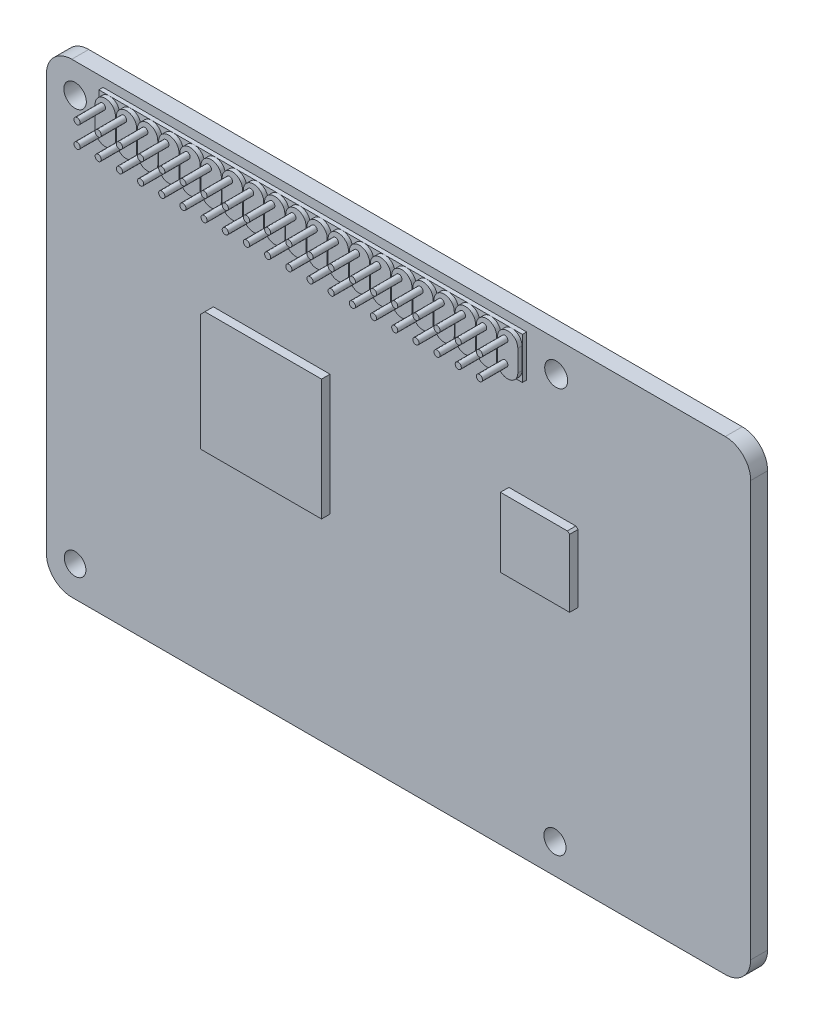
SolidWorks part; units mm, degrees
ref_plane "Plan de face" through (0, 0, 0) normal (0, 0, 1) x (1, 0, 0)
ref_plane "Plan de dessus" through (0, 0, 0) normal (0, 1, 0) x (1, 0, 0)
ref_plane "Plan de droite" through (0, 0, 0) normal (1, 0, 0) x (0, 0, -1)
sketch "Esquisse13" plane through (0, 0, 0) normal (0, 0, 1) x (1, 0, 0)
  line L1 (32.3051, 231.7529) -> (109.4451, 231.7529)
  line L2 (29.3051, 228.7529) -> (29.3051, 179.7529)
  line L3 (32.3051, 176.7529) -> (109.4451, 176.7529)
  line L4 (112.4451, 228.7529) -> (112.4451, 179.7529)
  arc A0 (112.4451, 228.7529) -> (109.4451, 231.7529) centre (109.4451, 228.7529) ccw
  arc A1 (112.4451, 179.7529) -> (109.4451, 176.7529) centre (109.4451, 179.7529) cw
  arc A2 (32.3051, 176.7529) -> (29.3051, 179.7529) centre (32.3051, 179.7529) cw
  arc A3 (32.3051, 231.7529) -> (29.3051, 228.7529) centre (32.3051, 228.7529) ccw
  dimension "D1" = 3
  dimension "D2" = 55
  dimension "D3" = 83.14
extrude "Boss.-Extru.6" add sketch "Esquisse13" along normal blind 2 separate body
sketch "Esquisse18" plane through (0, 0, 2) normal (0, 0, 1) x (1, 0, 0)
  line L0 (37.2566, 229.5258) -> (37.2566, 226.9968) construction
  line L1 (38.4539, 229.5258) -> (38.4539, 226.9968)
  line L2 (36.0594, 229.5258) -> (36.0594, 226.9968)
  line L3 (39.7566, 229.5258) -> (39.7566, 226.9968) construction
  line L4 (40.9539, 229.5258) -> (40.9539, 226.9968)
  line L5 (38.5594, 229.5258) -> (38.5594, 226.9968)
  line L6 (42.2566, 229.5258) -> (42.2566, 226.9968) construction
  line L7 (43.4539, 229.5258) -> (43.4539, 226.9968)
  line L8 (41.0594, 229.5258) -> (41.0594, 226.9968)
  line L9 (44.7566, 229.5258) -> (44.7566, 226.9968) construction
  line L10 (45.9539, 229.5258) -> (45.9539, 226.9968)
  line L11 (43.5594, 229.5258) -> (43.5594, 226.9968)
  line L12 (47.2566, 229.5258) -> (47.2566, 226.9968) construction
  line L13 (48.4539, 229.5258) -> (48.4539, 226.9968)
  line L14 (46.0594, 229.5258) -> (46.0594, 226.9968)
  line L15 (49.7566, 229.5258) -> (49.7566, 226.9968) construction
  line L16 (50.9539, 229.5258) -> (50.9539, 226.9968)
  line L17 (48.5594, 229.5258) -> (48.5594, 226.9968)
  line L18 (52.2566, 229.5258) -> (52.2566, 226.9968) construction
  line L19 (53.4539, 229.5258) -> (53.4539, 226.9968)
  line L20 (51.0594, 229.5258) -> (51.0594, 226.9968)
  line L21 (54.7566, 229.5258) -> (54.7566, 226.9968) construction
  line L22 (55.9539, 229.5258) -> (55.9539, 226.9968)
  line L23 (53.5594, 229.5258) -> (53.5594, 226.9968)
  line L24 (57.2566, 229.5258) -> (57.2566, 226.9968) construction
  line L25 (58.4539, 229.5258) -> (58.4539, 226.9968)
  line L26 (56.0594, 229.5258) -> (56.0594, 226.9968)
  line L27 (59.7566, 229.5258) -> (59.7566, 226.9968) construction
  line L28 (60.9539, 229.5258) -> (60.9539, 226.9968)
  line L29 (58.5594, 229.5258) -> (58.5594, 226.9968)
  line L30 (62.2566, 229.5258) -> (62.2566, 226.9968) construction
  line L31 (63.4539, 229.5258) -> (63.4539, 226.9968)
  line L32 (61.0594, 229.5258) -> (61.0594, 226.9968)
  line L33 (64.7566, 229.5258) -> (64.7566, 226.9968) construction
  line L34 (65.9539, 229.5258) -> (65.9539, 226.9968)
  line L35 (63.5594, 229.5258) -> (63.5594, 226.9968)
  line L36 (67.2566, 229.5258) -> (67.2566, 226.9968) construction
  line L37 (68.4539, 229.5258) -> (68.4539, 226.9968)
  line L38 (66.0594, 229.5258) -> (66.0594, 226.9968)
  line L39 (69.7566, 229.5258) -> (69.7566, 226.9968) construction
  line L40 (70.9539, 229.5258) -> (70.9539, 226.9968)
  line L41 (68.5594, 229.5258) -> (68.5594, 226.9968)
  line L42 (72.2566, 229.5258) -> (72.2566, 226.9968) construction
  line L43 (73.4539, 229.5258) -> (73.4539, 226.9968)
  line L44 (71.0594, 229.5258) -> (71.0594, 226.9968)
  line L45 (74.7566, 229.5258) -> (74.7566, 226.9968) construction
  line L46 (75.9539, 229.5258) -> (75.9539, 226.9968)
  line L47 (73.5594, 229.5258) -> (73.5594, 226.9968)
  line L48 (77.2566, 229.5258) -> (77.2566, 226.9968) construction
  line L49 (78.4539, 229.5258) -> (78.4539, 226.9968)
  line L50 (76.0594, 229.5258) -> (76.0594, 226.9968)
  line L51 (79.7566, 229.5258) -> (79.7566, 226.9968) construction
  line L52 (80.9539, 229.5258) -> (80.9539, 226.9968)
  line L53 (78.5594, 229.5258) -> (78.5594, 226.9968)
  line L54 (82.2566, 229.5258) -> (82.2566, 226.9968) construction
  line L55 (83.4539, 229.5258) -> (83.4539, 226.9968)
  line L56 (81.0594, 229.5258) -> (81.0594, 226.9968)
  line L57 (84.7566, 229.5258) -> (84.7566, 226.9968) construction
  line L58 (85.9539, 229.5258) -> (85.9539, 226.9968)
  line L59 (83.5594, 229.5258) -> (83.5594, 226.9968)
  arc A0 (38.4539, 229.5258) -> (36.0594, 229.5258) centre (37.2566, 229.5258) ccw
  arc A1 (36.0594, 226.9968) -> (38.4539, 226.9968) centre (37.2566, 226.9968) ccw
  arc A2 (40.9539, 229.5258) -> (38.5594, 229.5258) centre (39.7566, 229.5258) ccw
  arc A3 (38.5594, 226.9968) -> (40.9539, 226.9968) centre (39.7566, 226.9968) ccw
  arc A4 (43.4539, 229.5258) -> (41.0594, 229.5258) centre (42.2566, 229.5258) ccw
  arc A5 (41.0594, 226.9968) -> (43.4539, 226.9968) centre (42.2566, 226.9968) ccw
  arc A6 (45.9539, 229.5258) -> (43.5594, 229.5258) centre (44.7566, 229.5258) ccw
  arc A7 (43.5594, 226.9968) -> (45.9539, 226.9968) centre (44.7566, 226.9968) ccw
  arc A8 (48.4539, 229.5258) -> (46.0594, 229.5258) centre (47.2566, 229.5258) ccw
  arc A9 (46.0594, 226.9968) -> (48.4539, 226.9968) centre (47.2566, 226.9968) ccw
  arc A10 (50.9539, 229.5258) -> (48.5594, 229.5258) centre (49.7566, 229.5258) ccw
  arc A11 (48.5594, 226.9968) -> (50.9539, 226.9968) centre (49.7566, 226.9968) ccw
  arc A12 (53.4539, 229.5258) -> (51.0594, 229.5258) centre (52.2566, 229.5258) ccw
  arc A13 (51.0594, 226.9968) -> (53.4539, 226.9968) centre (52.2566, 226.9968) ccw
  arc A14 (55.9539, 229.5258) -> (53.5594, 229.5258) centre (54.7566, 229.5258) ccw
  arc A15 (53.5594, 226.9968) -> (55.9539, 226.9968) centre (54.7566, 226.9968) ccw
  arc A16 (58.4539, 229.5258) -> (56.0594, 229.5258) centre (57.2566, 229.5258) ccw
  arc A17 (56.0594, 226.9968) -> (58.4539, 226.9968) centre (57.2566, 226.9968) ccw
  arc A18 (60.9539, 229.5258) -> (58.5594, 229.5258) centre (59.7566, 229.5258) ccw
  arc A19 (58.5594, 226.9968) -> (60.9539, 226.9968) centre (59.7566, 226.9968) ccw
  arc A20 (63.4539, 229.5258) -> (61.0594, 229.5258) centre (62.2566, 229.5258) ccw
  arc A21 (61.0594, 226.9968) -> (63.4539, 226.9968) centre (62.2566, 226.9968) ccw
  arc A22 (65.9539, 229.5258) -> (63.5594, 229.5258) centre (64.7566, 229.5258) ccw
  arc A23 (63.5594, 226.9968) -> (65.9539, 226.9968) centre (64.7566, 226.9968) ccw
  arc A24 (68.4539, 229.5258) -> (66.0594, 229.5258) centre (67.2566, 229.5258) ccw
  arc A25 (66.0594, 226.9968) -> (68.4539, 226.9968) centre (67.2566, 226.9968) ccw
  arc A26 (70.9539, 229.5258) -> (68.5594, 229.5258) centre (69.7566, 229.5258) ccw
  arc A27 (68.5594, 226.9968) -> (70.9539, 226.9968) centre (69.7566, 226.9968) ccw
  arc A28 (73.4539, 229.5258) -> (71.0594, 229.5258) centre (72.2566, 229.5258) ccw
  arc A29 (71.0594, 226.9968) -> (73.4539, 226.9968) centre (72.2566, 226.9968) ccw
  arc A30 (75.9539, 229.5258) -> (73.5594, 229.5258) centre (74.7566, 229.5258) ccw
  arc A31 (73.5594, 226.9968) -> (75.9539, 226.9968) centre (74.7566, 226.9968) ccw
  arc A32 (78.4539, 229.5258) -> (76.0594, 229.5258) centre (77.2566, 229.5258) ccw
  arc A33 (76.0594, 226.9968) -> (78.4539, 226.9968) centre (77.2566, 226.9968) ccw
  arc A34 (80.9539, 229.5258) -> (78.5594, 229.5258) centre (79.7566, 229.5258) ccw
  arc A35 (78.5594, 226.9968) -> (80.9539, 226.9968) centre (79.7566, 226.9968) ccw
  arc A36 (83.4539, 229.5258) -> (81.0594, 229.5258) centre (82.2566, 229.5258) ccw
  arc A37 (81.0594, 226.9968) -> (83.4539, 226.9968) centre (82.2566, 226.9968) ccw
  arc A38 (85.9539, 229.5258) -> (83.5594, 229.5258) centre (84.7566, 229.5258) ccw
  arc A39 (83.5594, 226.9968) -> (85.9539, 226.9968) centre (84.7566, 226.9968) ccw
  point P2 (37.2566, 228.2613)
  point P11 (39.7566, 228.2613)
  point P18 (42.2566, 228.2613)
  point P25 (44.7566, 228.2613)
  point P32 (47.2566, 228.2613)
  point P39 (49.7566, 228.2613)
  point P46 (52.2566, 228.2613)
  point P53 (54.7566, 228.2613)
  point P60 (57.2566, 228.2613)
  point P67 (59.7566, 228.2613)
  point P74 (62.2566, 228.2613)
  point P81 (64.7566, 228.2613)
  point P88 (67.2566, 228.2613)
  point P95 (69.7566, 228.2613)
  point P102 (72.2566, 228.2613)
  point P109 (74.7566, 228.2613)
  point P116 (77.2566, 228.2613)
  point P123 (79.7566, 228.2613)
  point P130 (82.2566, 228.2613)
  point P137 (84.7566, 228.2613)
  dimension "D1" = 20
extrude "Boss.-Extru.8" add sketch "Esquisse18" along normal blind 1
sketch "Esquisse19" plane through (0, 0, 2) normal (0, 0, 1) x (1, 0, 0)
  line L1 (35.9943, 230.7231) -> (85.9948, 230.7231)
  line L2 (35.9943, 230.7231) -> (35.9943, 225.7996)
  line L3 (35.9943, 225.7996) -> (85.9948, 225.7996)
  line L4 (85.9948, 230.7231) -> (85.9948, 225.7996)
  arc A0 (36.0594, 226.9968) -> (38.4539, 226.9968) centre (37.2566, 226.9968) ccw construction
  arc A1 (38.4539, 229.5258) -> (36.0594, 229.5258) centre (37.2566, 229.5258) ccw construction
extrude "Boss.-Extru.9" add sketch "Esquisse19" along normal blind 0.5
sketch "Esquisse20" plane through (0, 0, 3) normal (0, 0, 1) x (1, 0, 0)
  line L0 (36.9236, 229.735) -> (36.9236, 227.2302) construction
  circle A0 centre (36.9236, 229.735) radius 0.3614
  circle A1 centre (36.9236, 227.2302) radius 0.3614
  circle A2 centre (39.4236, 229.735) radius 0.3614
  circle A3 centre (39.4236, 227.2302) radius 0.3614
  circle A4 centre (41.9236, 229.735) radius 0.3614
  circle A5 centre (41.9236, 227.2302) radius 0.3614
  circle A6 centre (44.4236, 229.735) radius 0.3614
  circle A7 centre (44.4236, 227.2302) radius 0.3614
  circle A8 centre (46.9236, 229.735) radius 0.3614
  circle A9 centre (46.9236, 227.2302) radius 0.3614
  circle A10 centre (49.4236, 229.735) radius 0.3614
  circle A11 centre (49.4236, 227.2302) radius 0.3614
  circle A12 centre (51.9236, 229.735) radius 0.3614
  circle A13 centre (51.9236, 227.2302) radius 0.3614
  circle A14 centre (54.4236, 229.735) radius 0.3614
  circle A15 centre (54.4236, 227.2302) radius 0.3614
  circle A16 centre (56.9236, 229.735) radius 0.3614
  circle A17 centre (56.9236, 227.2302) radius 0.3614
  circle A18 centre (59.4236, 229.735) radius 0.3614
  circle A19 centre (59.4236, 227.2302) radius 0.3614
  circle A20 centre (61.9236, 229.735) radius 0.3614
  circle A21 centre (61.9236, 227.2302) radius 0.3614
  circle A22 centre (64.4236, 229.735) radius 0.3614
  circle A23 centre (64.4236, 227.2302) radius 0.3614
  circle A24 centre (66.9236, 229.735) radius 0.3614
  circle A25 centre (66.9236, 227.2302) radius 0.3614
  circle A26 centre (69.4236, 229.735) radius 0.3614
  circle A27 centre (69.4236, 227.2302) radius 0.3614
  circle A28 centre (71.9236, 229.735) radius 0.3614
  circle A29 centre (71.9236, 227.2302) radius 0.3614
  circle A30 centre (74.4236, 229.735) radius 0.3614
  circle A31 centre (74.4236, 227.2302) radius 0.3614
  circle A32 centre (76.9236, 229.735) radius 0.3614
  circle A33 centre (76.9236, 227.2302) radius 0.3614
  circle A34 centre (79.4236, 229.735) radius 0.3614
  circle A35 centre (79.4236, 227.2302) radius 0.3614
  circle A36 centre (81.9236, 229.735) radius 0.3614
  circle A37 centre (81.9236, 227.2302) radius 0.3614
  circle A38 centre (84.4236, 229.735) radius 0.3614
  circle A39 centre (84.4236, 227.2302) radius 0.3614
  dimension "D1" = 20
extrude "Boss.-Extru.10" add sketch "Esquisse20" along normal blind 3
sketch "Esquisse21" plane through (0, 0, 2) normal (0, 0, 1) x (1, 0, 0)
  line L0 (48.4885, 214.2688) -> (49.0165, 214.7968)
  line L1 (62.7885, 200.4968) -> (48.4885, 200.4968)
  line L2 (62.7885, 200.4968) -> (62.7885, 214.7968)
  line L3 (62.7885, 214.7968) -> (49.0165, 214.7968)
  line L4 (48.4885, 200.4968) -> (48.4885, 214.2688)
  line L5 (91.8038, 213.7838) -> (92.0748, 213.5724)
  line L6 (83.9048, 205.5938) -> (92.0748, 205.5938)
  line L7 (83.9048, 205.5938) -> (83.9048, 213.7838)
  line L8 (83.9048, 213.7838) -> (91.8038, 213.7838)
  line L9 (92.0748, 205.5938) -> (92.0748, 213.5724)
  dimension "D1" = 14.3
  dimension "D2" = 14.3
  dimension "D3" = 8.17
  dimension "D4" = 8.19
extrude "Boss.-Extru.11" add sketch "Esquisse21" along normal blind 1
sketch "Esquisse22" plane through (0, 0, 0) normal (0, 0, -1) x (-1, 0, 0)
  line L0 (-77.9075, 215.1199) -> (-77.5535, 215.4739)
  line L1 (-65.8326, 203.3272) -> (-77.9075, 203.3272)
  line L2 (-65.8326, 203.3272) -> (-65.8326, 215.4739)
  line L3 (-65.8326, 215.4739) -> (-77.5535, 215.4739)
  line L4 (-77.9075, 203.3272) -> (-77.9075, 215.1199)
extrude "Boss.-Extru.12" add sketch "Esquisse22" along normal blind 1
sketch "Esquisse23" plane through (0, 0, 2) normal (0, 0, 1) x (1, 0, 0)
  circle A0 centre (32.6941, 228.256) radius 1.3282
  circle A1 centre (32.6941, 180.3609) radius 1.2739
  circle A2 centre (89.3389, 180.2903) radius 1.3076
  circle A3 centre (89.4851, 228.1459) radius 1.3542
extrude "Enlèv. mat.-Extru.1" cut sketch "Esquisse23" against normal blind 21
sketch "Esquisse24" plane through (0, 0, 0) normal (0, 0, -1) x (-1, 0, 0)
  line L1 (-41.9599, 209.7105) -> (-30.4379, 209.7105)
  line L2 (-41.9599, 209.7105) -> (-41.9599, 198.5462)
  line L3 (-41.9599, 198.5462) -> (-30.4379, 198.5462)
  line L4 (-30.4379, 209.7105) -> (-30.4379, 198.5462)
extrude "Boss.-Extru.13" add sketch "Esquisse24" along normal blind 0.6
sketch "Esquisse25" plane through (30.4379, 0, 0) normal (-1, 0, 0) x (0, 0, 1)
  line L1 (-0.5, 209.6213) -> (0, 209.6213)
  line L2 (-0.5, 209.6213) -> (-0.5, 198.6213)
  line L3 (-0.5, 198.6213) -> (0, 198.6213)
  line L4 (0, 209.6213) -> (0, 198.6213)
  line L5 (0, 228.7529) -> (0, 179.7529) construction
  line L6 (0, 198.5462) -> (0, 209.7105) construction
  line L7 (0, 203.3272) -> (0, 215.4739) construction
  dimension "D1" = 0.5
  dimension "D2" = 11
extrude "Enlèv. mat.-Extru.2" cut sketch "Esquisse25" against normal blind 11
